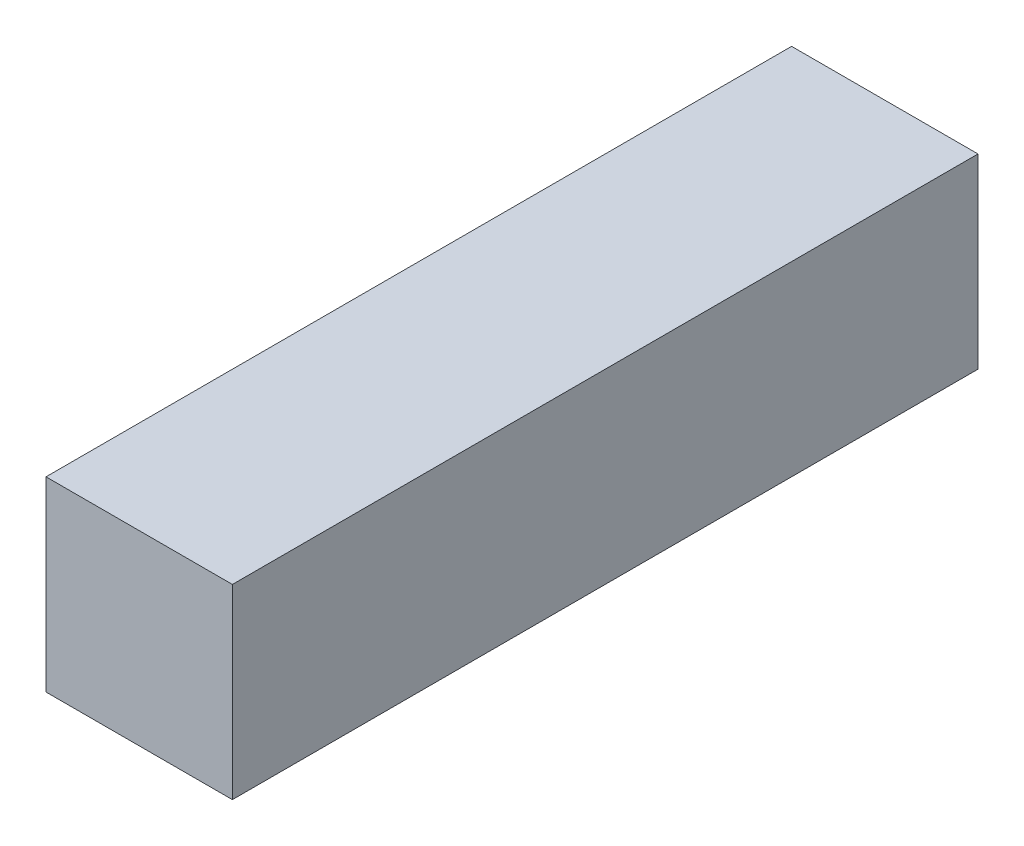
SolidWorks part; units mm, degrees
ref_plane "Front Plane" through (0, 0, 0) normal (0, 0, 1) x (1, 0, 0)
ref_plane "Top Plane" through (0, 0, 0) normal (0, 1, 0) x (1, 0, 0)
ref_plane "Right Plane" through (0, 0, 0) normal (1, 0, 0) x (0, 0, -1)
sketch "Sketch1" plane through (0, 0, 0) normal (0, 0, 1) x (1, 0, 0)
  line L1 (-3.175, 3.175) -> (3.175, 3.175)
  line L2 (-3.175, 3.175) -> (-3.175, -3.175)
  line L3 (-3.175, -3.175) -> (3.175, -3.175)
  line L4 (3.175, 3.175) -> (3.175, -3.175)
  line L5 (-3.175, 3.175) -> (3.175, -3.175) construction
  line L6 (-3.175, -3.175) -> (3.175, 3.175) construction
  point P0 (0, 0)
  dimension "D1" = 6.35
  dimension "D2" = 6.35
extrude "Boss-Extrude1" add sketch "Sketch1" along normal blind 25.4
